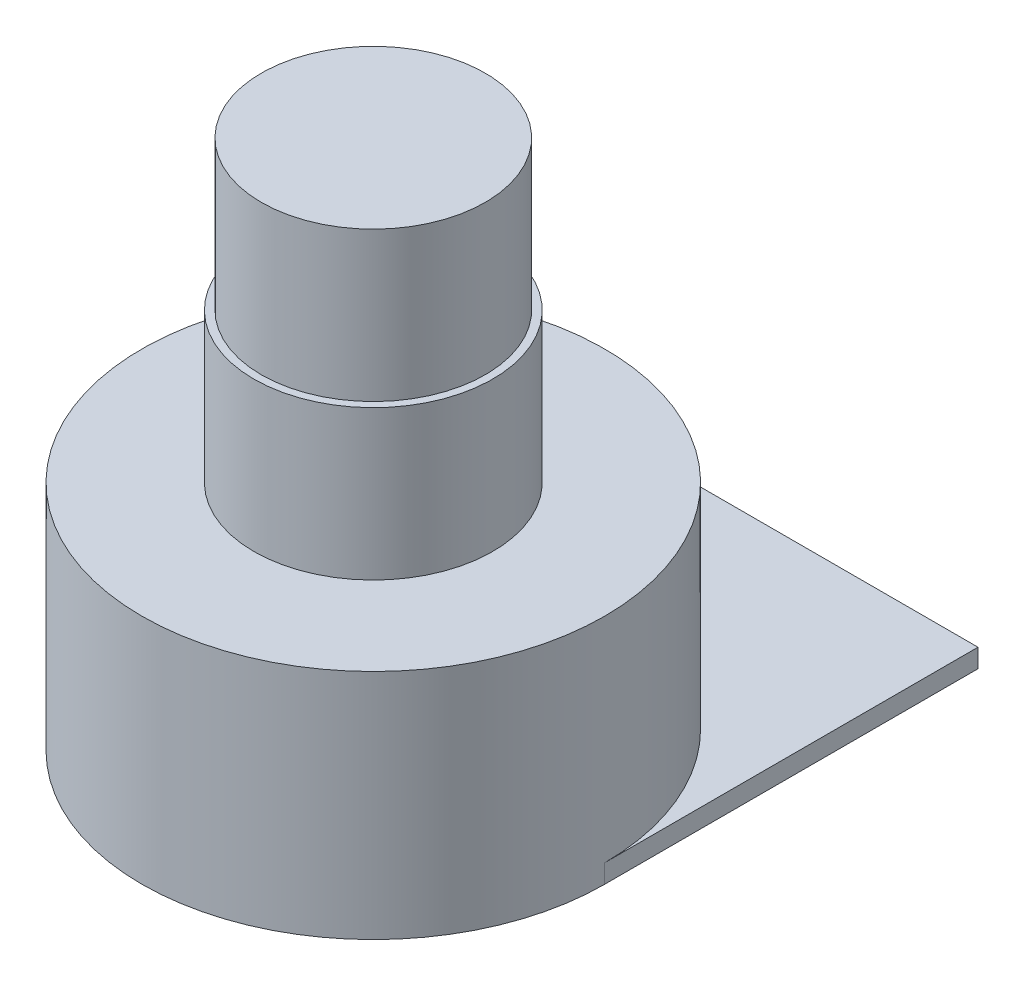
SolidWorks part; units mm, degrees
ref_plane "Спереди" through (0, 0, 0) normal (0, 0, 1) x (1, 0, 0)
ref_plane "Сверху" through (0, 0, 0) normal (0, 1, 0) x (1, 0, 0)
ref_plane "Справа" through (0, 0, 0) normal (1, 0, 0) x (0, 0, -1)
sketch "Эскиз1" plane through (0, 0, 0) normal (0, 1, 0) x (1, 0, 0)
  circle A0 centre (0, 0) radius 6.2
extrude "Вытянуть1" add sketch "Эскиз1" along normal blind 6.22
sketch "Эскиз2" plane through (0, 0, 0) normal (0, -1, 0) x (1, 0, 0)
  line L2 (-6.2, 0) -> (-6.2, -10)
  line L3 (-6.2, -10) -> (6.2, -10)
  line L4 (6.2, 0) -> (6.2, -10)
  arc A0 (6.2, 0) -> (-6.2, 0) centre (0, 0) ccw
extrude "Вытянуть2" add sketch "Эскиз2" along normal blind 0.5 from offset 0.5
sketch "Эскиз3" plane through (0, 6.22, 0) normal (0, 1, 0) x (1, 0, 0)
  circle A0 centre (0, 0) radius 3.2
extrude "Вытянуть3" add sketch "Эскиз3" along normal blind 4
sketch "Эскиз4" plane through (0, 10.22, 0) normal (0, 1, 0) x (-1, 0, 0)
  circle A0 centre (0, 0) radius 3
extrude "Вытянуть4" add sketch "Эскиз4" along normal blind 4
